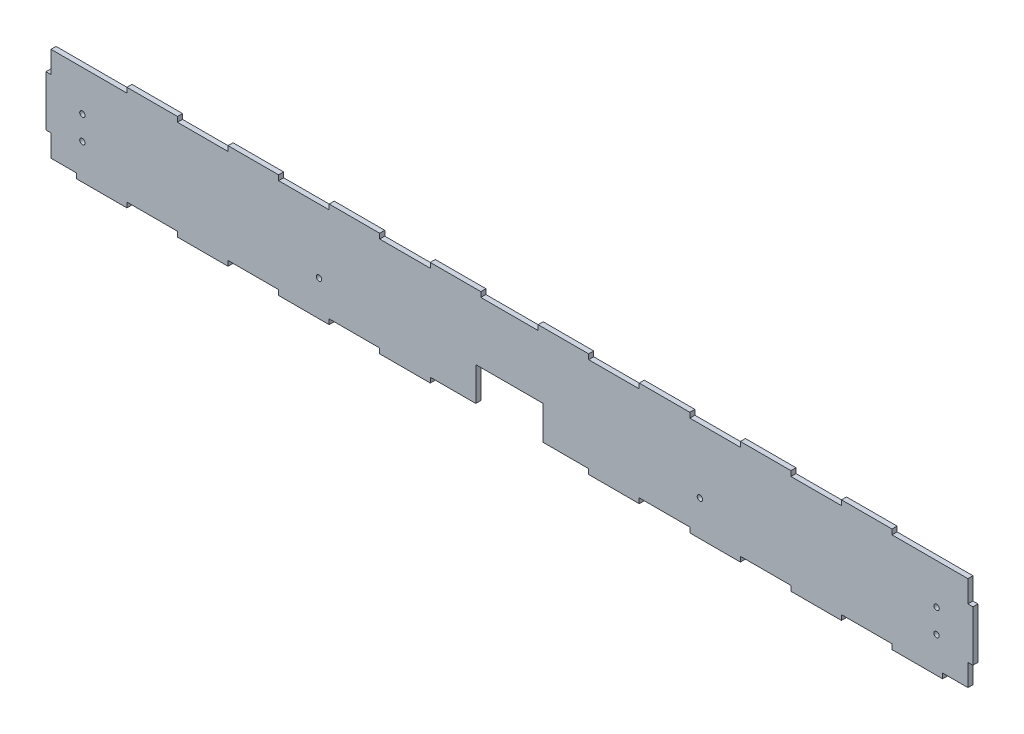
SolidWorks part; units mm, degrees
ref_plane "Front Plane" through (0, 0, 0) normal (0, 0, 1) x (1, 0, 0)
ref_plane "Top Plane" through (0, 0, 0) normal (0, 1, 0) x (1, 0, 0)
ref_plane "Right Plane" through (0, 0, 0) normal (1, 0, 0) x (0, 0, -1)
sketch "Sketch1" plane through (0, 0, 0) normal (0, 0, 1) x (1, 0, 0)
  line L1 (0, -28) -> (272, -28)
  line L2 (0, -28) -> (0, 28)
  line L3 (0, 28) -> (272, 28)
  line L4 (272, -28) -> (272, 28)
  dimension "D1" = 272
  dimension "D2" = 56
extrude "Boss-Extrude1" add sketch "Sketch1" along normal blind 3
sketch "Sketch4" plane through (0, 0, 3) normal (0, 0, 1) x (1, 0, 0)
  line L0 (253.41, 4.02) -> (253.41, -10.06) construction
  line L2 (272, -28) -> (272, 28) construction
  line L3 (272, 28) -> (0, 28) construction
  line L4 (253.41, -10.06) -> (113, -10.06) construction
  line L5 (0, -28) -> (20, -28)
  line L6 (0, -28) -> (0, -8)
  line L7 (0, -8) -> (20, -8)
  line L8 (20, -28) -> (20, -8)
  circle A4 centre (253.41, -10.06) radius 1.6
  circle A5 centre (253.41, 4.02) radius 1.6
  circle A6 centre (113, -10.06) radius 1.6
  dimension "D3" = 3.2
  dimension "D1" = 14.08
  dimension "D2" = 140.41
  dimension "D4" = 18.59
  dimension "D5" = 23.98
  dimension "D6" = 20
  dimension "D7" = 20
extrude "Cut-Extrude1" cut sketch "Sketch4" against normal up to next
sketch "Sketch5" plane through (0, 0, 0) normal (0, 0, 1) x (1, 0, 0)
  line L0 (272, -28) -> (272, 28) construction
  line L1 (272, 15) -> (275, 15)
  line L2 (272, 15) -> (272, -15)
  line L3 (272, -15) -> (275, -15)
  line L4 (275, 15) -> (275, -15)
  line L5 (272, 28) -> (0, 28) construction
  line L6 (227, 28) -> (197, 28)
  line L7 (227, 28) -> (227, 31)
  line L8 (227, 31) -> (197, 31)
  line L9 (197, 28) -> (197, 31)
  line L10 (167, 28) -> (167, 31)
  line L11 (167, 28) -> (137, 28)
  line L12 (137, 28) -> (137, 31)
  line L13 (167, 31) -> (137, 31)
  line L14 (107, 28) -> (107, 31)
  line L15 (107, 28) -> (77, 28)
  line L16 (77, 28) -> (77, 31)
  line L17 (107, 31) -> (77, 31)
  line L18 (47, 28) -> (47, 31)
  line L19 (47, 28) -> (17, 28)
  line L20 (17, 28) -> (17, 31)
  line L21 (47, 31) -> (17, 31)
  line L22 (20, -28) -> (272, -28) construction
  line L23 (257, -28) -> (227, -28)
  line L24 (257, -28) -> (257, -31)
  line L25 (257, -31) -> (227, -31)
  line L26 (227, -28) -> (227, -31)
  line L27 (197, -28) -> (197, -31)
  line L28 (197, -28) -> (167, -28)
  line L29 (167, -28) -> (167, -31)
  line L30 (197, -31) -> (167, -31)
  line L31 (137, -28) -> (137, -31)
  line L32 (137, -28) -> (107, -28)
  line L33 (107, -28) -> (107, -31)
  line L34 (137, -31) -> (107, -31)
  line L35 (77, -28) -> (77, -31)
  line L36 (77, -28) -> (47, -28)
  line L37 (47, -28) -> (47, -31)
  line L38 (77, -31) -> (47, -31)
  point P6 (272, 0)
  dimension "D1" = 3
  dimension "D2" = 30
  dimension "D3" = 30
  dimension "D4" = 3
  dimension "D5" = 45
  dimension "D7" = 30
  dimension "D8" = 3
  dimension "D9" = 15
  dimension "D6" = 4
  dimension "D10" = 4
extrude "Boss-Extrude2" add sketch "Sketch5" along normal blind 3
mirror "Mirror1" about plane through (0, -28, 3) normal (1, 0, 0) of bodies 103
